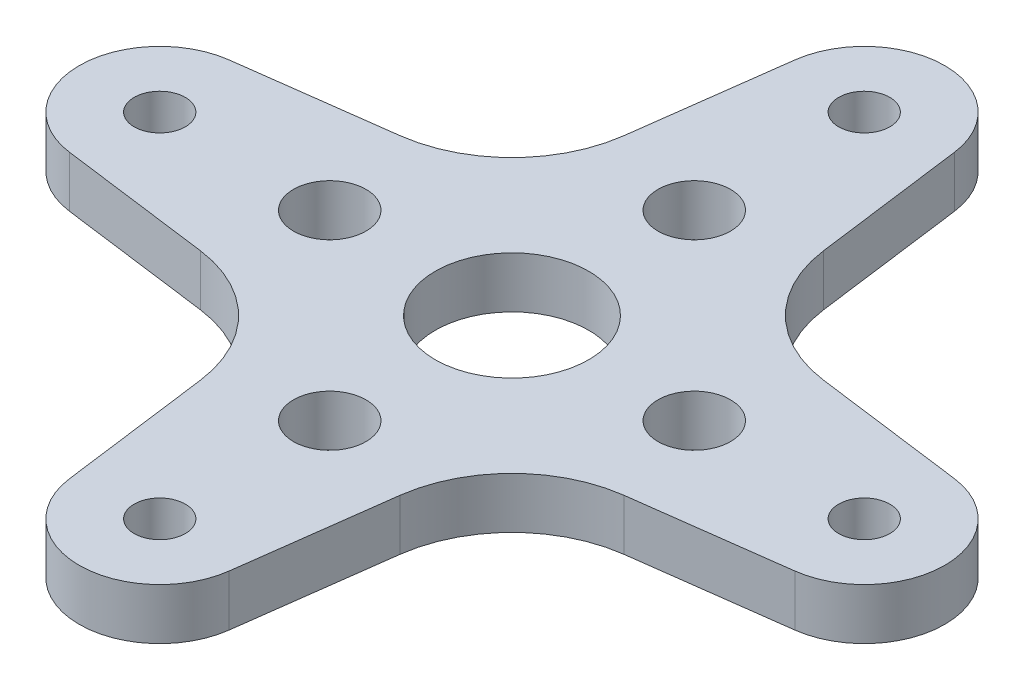
SolidWorks part; units mm, degrees
material "7075-T6, Plate (SS)"
ref_plane "Front Plane" through (0, 0, 0) normal (0, 0, 1) x (1, 0, 0)
ref_plane "Top Plane" through (0, 0, 0) normal (0, 1, 0) x (1, 0, 0)
ref_plane "Right Plane" through (0, 0, 0) normal (1, 0, 0) x (0, 0, -1)
sketch "Sketch1" plane through (0, 0, 0) normal (0, 1, 0) x (1, 0, 0)
  line L0 (0, 0) -> (0, 21.8652) construction
  line L1 (0, 0) -> (14.1869, 14.1869) construction
  line L2 (4.9572, 22.5178) -> (6.1926, 13.1344)
  line L3 (22.5178, -4.9572) -> (13.1344, -6.1926)
  line L4 (22.5178, 4.9572) -> (13.1344, 6.1926)
  line L5 (0, 0) -> (-14.1869, 14.1869) construction
  line L8 (-4.9572, 22.5178) -> (-6.1926, 13.1344)
  line L9 (-8.4853, 8.4853) -> (8.4853, -8.4853)
  arc A0 (-4.9572, 22.5178) -> (4.9572, 22.5178) centre (0, 21.8652) cw
  arc A1 (6.1926, 13.1344) -> (13.1344, 6.1926) centre (14.1869, 14.1869) ccw
  arc A2 (-6.1926, 13.1344) -> (-8.4853, 8.4853) centre (-14.1869, 14.1869) cw
  arc A3 (13.1344, -6.1926) -> (8.4853, -8.4853) centre (14.1869, -14.1869) ccw
  arc A4 (22.5178, -4.9572) -> (22.5178, 4.9572) centre (21.8652, 0) ccw
  point P18 (8.4853, 8.4853)
  dimension "D5" = 5
  dimension "D1" = 21.8652
  dimension "D2" = 45
  dimension "D3" = 12
  dimension "D4" = 7.5
extrude "Boss-Extrude1" add sketch "Sketch1" along normal blind 3.175
mirror "Mirror7" about plane through (-8.4853, 3.175, -8.4853) normal (0.7071, 0, -0.7071) of "Boss-Extrude1"
hole_wizard "1/8 (0.1250) Dowel Hole1" positions "Sketch2" profile "Sketch3" hole size "1/8" standard "ANSI Inch" end condition through all
sketch "Sketch2" plane through (0, 3.175, 0) normal (0, 1, 0) x (1, 0, 0)
  point P0 (0, 21.8652)
  point P3 (0, -21.8652)
  point P6 (-21.8652, 0)
  point P9 (21.8652, 0)
sketch "Sketch3" plane through (0, 3.175, -21.8652) normal (1, 0, 0) x (0, 0, 1)
  line L0 (0, 0) -> (0, 3.175)
  line L1 (0, 3.175) -> (1.5875, 3.175)
  line L2 (1.5875, 3.175) -> (1.5875, 0)
  line L5 (1.5875, 0) -> (0, 0)
  line L11 (0, -6.35) -> (0, 107.95) construction
  dimension "Thru Hole Dia." = 3.175
  dimension "Thru Hole Depth" = 3.175
sketch "Sketch4" plane through (0, 3.175, 0) normal (0, 1, 0) x (1, 0, 0)
  circle A0 centre (0, 0) radius 4.7625
  dimension "D1" = 9.525
extrude "Cut-Extrude1" cut sketch "Sketch4" against normal through all
hole_wizard "M4 Clearance Hole1" positions "Sketch5" profile "Sketch6" hole size "M4" standard "ANSI Metric" end condition through all
sketch "Sketch5" plane through (0, 3.175, 0) normal (0, 1, 0) x (1, 0, 0)
  line L0 (0, 0) -> (0, 11.3137) construction
  line L2 (0, 0) -> (11.3137, 0) construction
  circle A0 centre (0, 0) radius 11.3137 construction
  point P7 (0, 11.3137)
  point P12 (11.3137, 0)
  point P19 (0, -11.3137)
  point P21 (-11.3137, 0)
  point P24 (0, 0)
  dimension "D1" = 16
sketch "Sketch6" plane through (-11.3137, 3.175, 0) normal (1, 0, 0) x (0, 0, 1)
  line L0 (0, 0) -> (0, 3.175)
  line L1 (0, 3.175) -> (2.25, 3.175)
  line L2 (2.25, 3.175) -> (2.25, 0)
  line L5 (2.25, 0) -> (0, 0)
  line L11 (0, -6.35) -> (0, 107.95) construction
  dimension "Thru Hole Dia." = 4.5
  dimension "Thru Hole Depth" = 3.175
equation "\"0.25iin\"=10"
